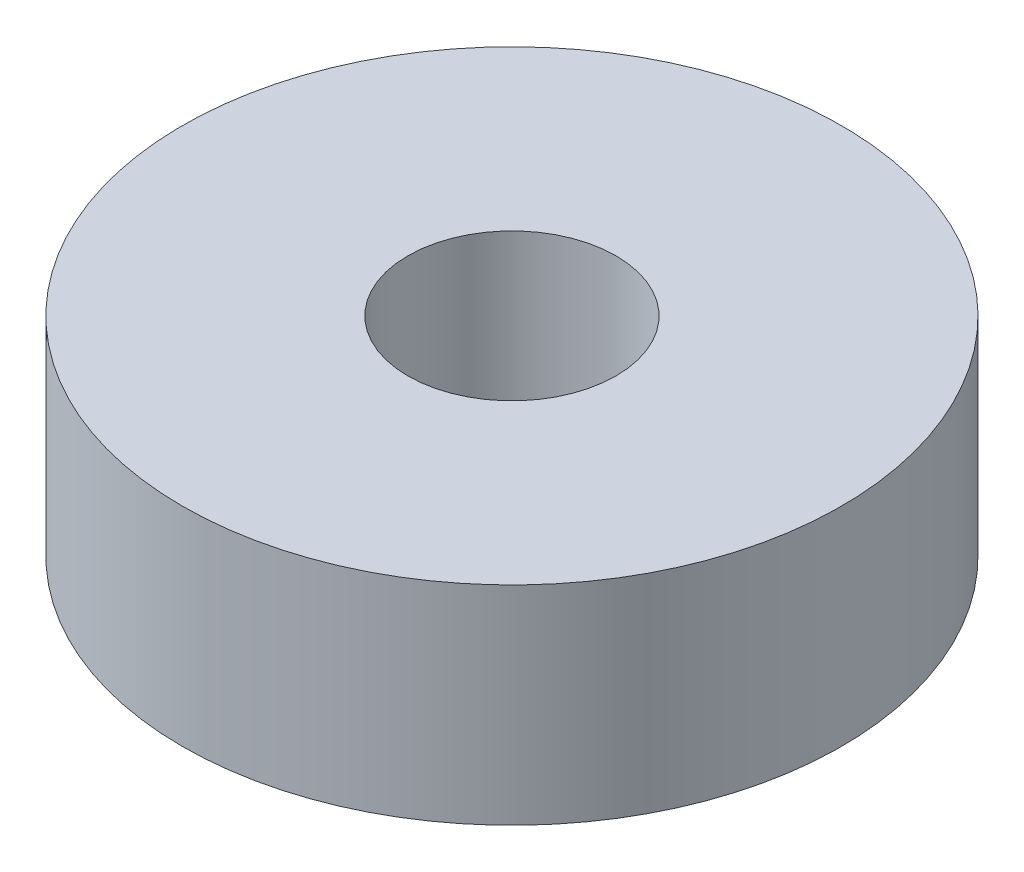
SolidWorks part; units mm, degrees
ref_plane "Front Plane" through (0, 0, 0) normal (0, 0, 1) x (1, 0, 0)
ref_plane "Top Plane" through (0, 0, 0) normal (0, 1, 0) x (1, 0, 0)
ref_plane "Right Plane" through (0, 0, 0) normal (1, 0, 0) x (0, 0, -1)
sketch "Sketch1" plane through (0, 0, 0) normal (0, 1, 0) x (1, 0, 0)
  circle A0 centre (0, 0) radius 9.5
  circle A1 centre (0, 0) radius 3
  dimension "D1" = 19
  dimension "D2" = 6
extrude "Boss-Extrude1" add sketch "Sketch1" along normal blind 6
